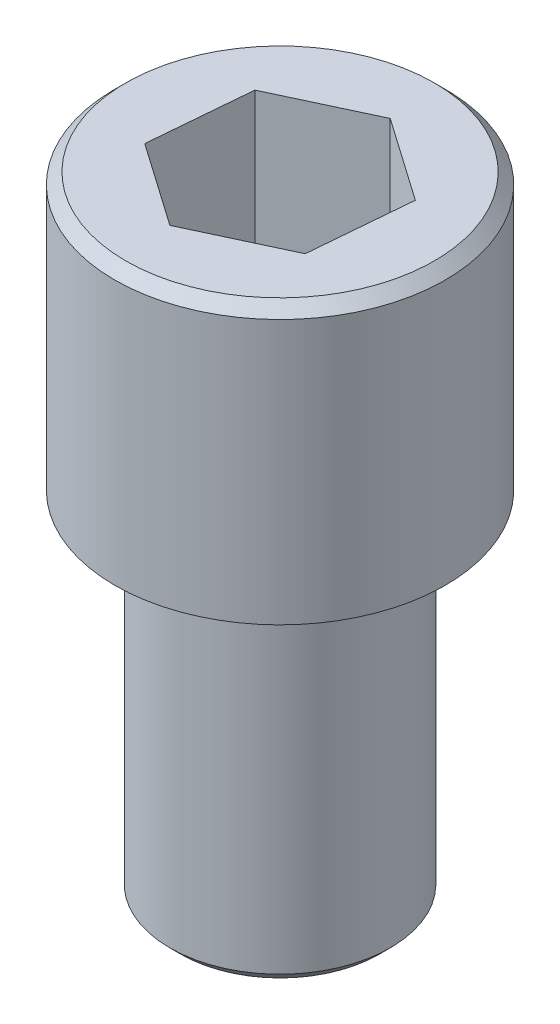
SolidWorks part; units mm, degrees
ref_plane "Přední rovina" through (0, 0, 0) normal (0, 0, 1) x (1, 0, 0)
ref_plane "Horní rovina" through (0, 0, 0) normal (0, 1, 0) x (1, 0, 0)
ref_plane "Pravá rovina" through (0, 0, 0) normal (1, 0, 0) x (0, 0, -1)
sketch "Skica1" plane through (0, 0, 0) normal (0, 1, 0) x (1, 0, 0)
  circle A0 centre (0, 0) radius 2.5
  dimension "D1" = 5
extrude "Přidat vysunutím1" add sketch "Skica1" along normal blind 8
sketch "Skica2" plane through (0, 8, 0) normal (0, 1, 0) x (1, 0, 0)
  circle A0 centre (0, 0) radius 3.75
  dimension "D1" = 7.5
extrude "Přidat vysunutím2" add sketch "Skica2" along normal blind 6.25
sketch "Skica3" plane through (0, 14.25, 0) normal (0, 1, 0) x (1, 0, 0)
  line L1 (-0.1991, -2.3008) -> (1.893, -1.3228)
  line L2 (1.893, -1.3228) -> (2.0921, 0.978)
  line L3 (2.0921, 0.978) -> (0.1991, 2.3008)
  line L4 (0.1991, 2.3008) -> (-1.893, 1.3228)
  line L5 (-1.893, 1.3228) -> (-2.0921, -0.978)
  line L6 (-2.0921, -0.978) -> (-0.1991, -2.3008)
  circle A0 centre (0, 0) radius 2 construction
  dimension "D1" = 4
extrude "Odebrat vysunutím1" cut sketch "Skica3" against normal blind 3.75
chamfer "Zkosení1" distance 0.25 angle 45 2 edges at (0, 0, 2.5) (0, 14.25, 3.75)
